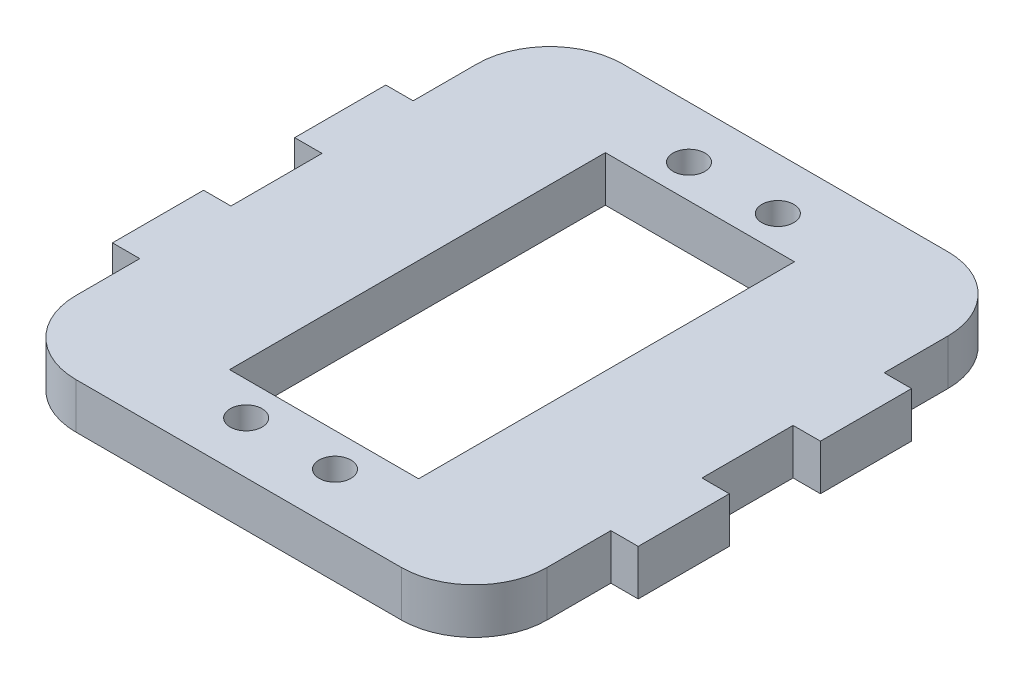
SolidWorks part; units mm, degrees
ref_plane "前视基准面" through (0, 0, 0) normal (0, 0, 1) x (1, 0, 0)
ref_plane "上视基准面" through (0, 0, 0) normal (0, 1, 0) x (1, 0, 0)
ref_plane "右视基准面" through (0, 0, 0) normal (1, 0, 0) x (0, 0, -1)
sketch "草图1" plane through (0, 0, 0) normal (0, 1, 0) x (1, 0, 0)
  line L0 (-426.4128, 0) -> (20894.2285, 0) construction
  line L1 (0, -426.4128) -> (0, 20894.2285) construction
  line L2 (25.85, -30) -> (-25.85, -30)
  line L3 (-25.85, -30) -> (-25.85, -15)
  line L4 (25.85, 30) -> (-25.85, 30)
  line L5 (25.85, -30) -> (25.85, -15)
  line L6 (-10.375, 20.625) -> (-10.375, -20.625)
  line L7 (-10.375, -20.625) -> (10.375, -20.625)
  line L8 (-10.375, 20.625) -> (10.375, 20.625)
  line L9 (10.375, 20.625) -> (10.375, -20.625)
  line L10 (-25.85, -15) -> (-28.85, -15)
  line L11 (-28.85, -15) -> (-28.85, -5)
  line L12 (-28.85, -5) -> (-25.85, -5)
  line L13 (-28.85, 5) -> (-25.85, 5)
  line L14 (-28.85, 15) -> (-28.85, 5)
  line L15 (-25.85, 15) -> (-28.85, 15)
  line L16 (25.85, 15) -> (28.85, 15)
  line L17 (28.85, 15) -> (28.85, 5)
  line L18 (28.85, 5) -> (25.85, 5)
  line L19 (28.85, -5) -> (25.85, -5)
  line L20 (28.85, -15) -> (28.85, -5)
  line L21 (25.85, -15) -> (28.85, -15)
  line L22 (-25.85, -5) -> (-25.85, 5)
  line L23 (-25.85, 15) -> (-25.85, 30)
  line L24 (25.85, -5) -> (25.85, 5)
  line L25 (25.85, 15) -> (25.85, 30)
  circle A0 centre (-4.875, -24.3) radius 1.75
  circle A1 centre (4.875, -24.3) radius 1.75
  circle A2 centre (4.875, 24.3) radius 1.75
  circle A3 centre (-4.875, 24.3) radius 1.75
  point P4 (25.85, 0)
  point P9 (-25.85, 0)
  point P11 (0, 30)
  point P12 (0, -30)
  point P16 (10.375, 0)
  point P18 (-10.375, 0)
  point P19 (0, 20.625)
  point P20 (0, -20.625)
  dimension "D5" = 3.5
  dimension "D1" = 60
  dimension "D2" = 51.7
  dimension "D3" = 41.25
  dimension "D4" = 20.75
  dimension "D6" = 9.75
  dimension "D7" = 48.6
  dimension "D8" = 10
  dimension "D9" = 10
  dimension "D10" = 3
extrude "凸台-拉伸1" add sketch "草图1" along normal blind 5
fillet "圆角1" radius 8 4 edges at (25.85, 2.5, 30) (-25.85, 2.5, 30) (-25.85, 2.5, -30) (25.85, 2.5, -30)
